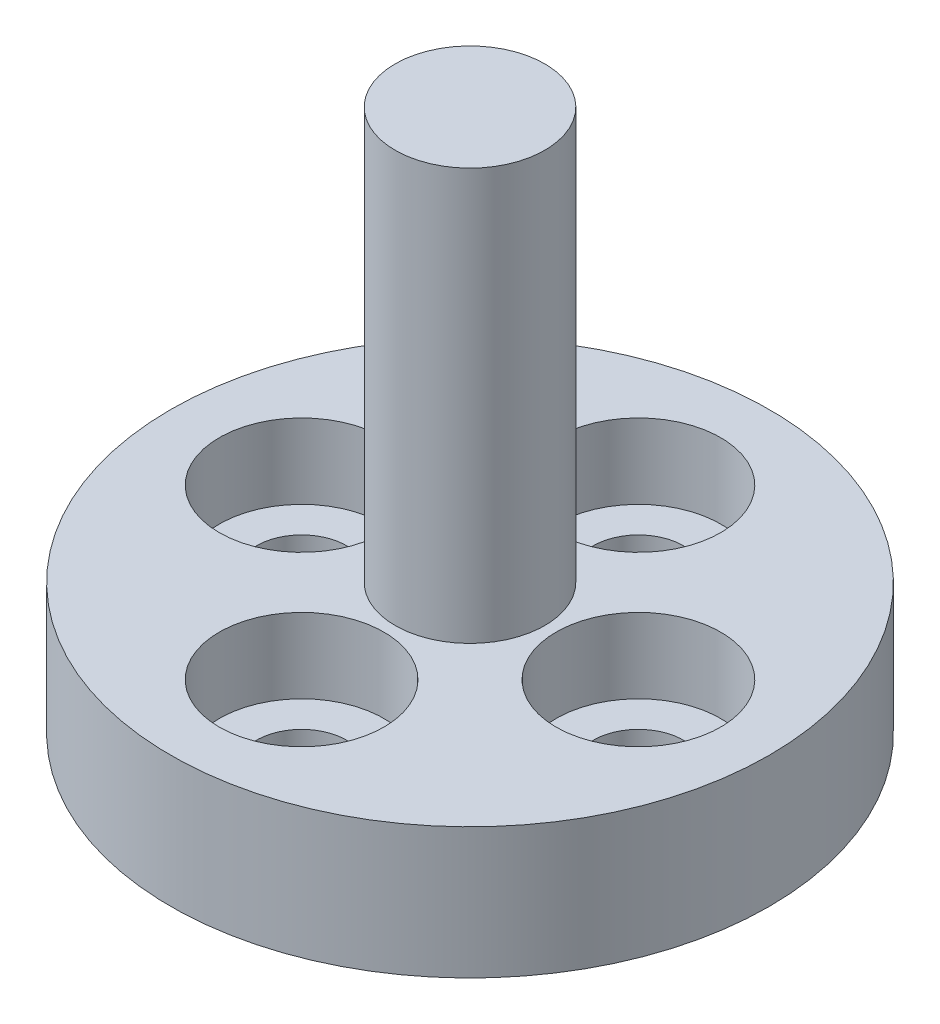
SolidWorks part; units mm, degrees
ref_plane "Front Plane" through (0, 0, 0) normal (0, 0, 1) x (1, 0, 0)
ref_plane "Top Plane" through (0, 0, 0) normal (0, 1, 0) x (1, 0, 0)
ref_plane "Right Plane" through (0, 0, 0) normal (1, 0, 0) x (0, 0, -1)
sketch "Sketch1" plane through (0, 0, 0) normal (0, 0, 1) x (1, 0, 0)
  line L0 (0, 0) -> (8, 0)
  line L1 (8, 0) -> (8, 3.5)
  line L2 (8, 3.5) -> (2, 3.5)
  line L3 (2, 3.5) -> (2, 14.5)
  line L4 (2, 14.5) -> (0, 14.5)
  line L5 (0, 14.5) -> (0, 0)
  dimension "D1" = 8
  dimension "D2" = 14.5
  dimension "D3" = 2
  dimension "D4" = 11
revolve "Revolve1" add sketch "Sketch1" angle 360 about L5
sketch "Sketch2" plane through (0, 3.5, 0) normal (0, 1, 0) x (1, 0, 0)
  circle A0 centre (0, 0) radius 4.5
  dimension "D1" = 9
hole_wizard "CBORE for M2 SHCS1" positions "Sketch3" profile "Sketch4" counterbore size "M2" standard "ANSI Metric" end condition through all
sketch "Sketch3" plane through (0, 3.5, 0) normal (0, 1, 0) x (1, 0, 0)
  circle A0 centre (0, 0) radius 4.5 construction
  point P0 (-4.5, 0)
  point P4 (0, 4.5)
  point P6 (4.5, 0)
  point P8 (0, -4.5)
sketch "Sketch4" plane through (-4.5, 3.5, 0) normal (1, 0, 0) x (0, 0, 1)
  line L0 (0, 0) -> (0, 3.5)
  line L1 (0, 3.5) -> (1.2, 3.5)
  line L3 (1.2, 3.5) -> (1.2, 2)
  line L4 (1.2, 2) -> (2.2, 2)
  line L5 (2.2, 2) -> (2.2, 0)
  line L7 (2.2, 0) -> (0, 0)
  line L11 (0, -6.35) -> (0, 107.95) construction
  dimension "Thru Hole Dia." = 2.4
  dimension "Thru Hole Depth" = 3.5
  dimension "C'Bore Dia." = 4.4
  dimension "C'Bore Depth" = 2
